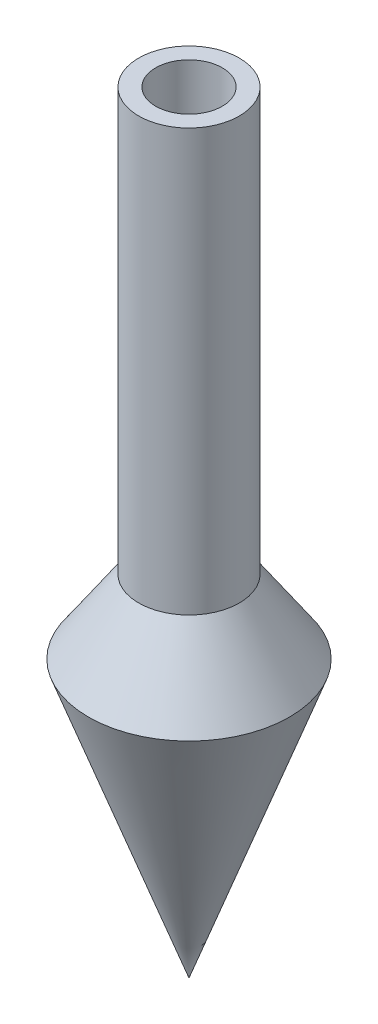
SolidWorks part; units mm, degrees
ref_plane "Front Plane" through (0, 0, 0) normal (0, 0, 1) x (1, 0, 0)
ref_plane "Top Plane" through (0, 0, 0) normal (0, 1, 0) x (1, 0, 0)
ref_plane "Right Plane" through (0, 0, 0) normal (1, 0, 0) x (0, 0, -1)
sketch "Sketch3" plane through (0, 0, 0) normal (0, 0, 1) x (1, 0, 0)
  line L0 (0, 0) -> (260.5989, 715.9895)
  line L1 (260.5989, 715.9895) -> (130.2994, 906.7875)
  line L2 (130.2994, 906.7875) -> (130.2994, 2000)
  line L5 (0, -730.4365) -> (0, 2203.2841) construction
  line L6 (0, 0) -> (0, 2000)
  line L7 (130.2994, 2000) -> (0, 2000)
  dimension "D1" = 2000
revolve "Revolve4" add sketch "Sketch3" angle 360 about L5
sketch "Sketch4" plane through (0, 2000, 0) normal (0, 1, 0) x (1, 0, 0)
  circle A0 centre (0, 0) radius 86.3632
extrude "Cut-Extrude1" cut sketch "Sketch4" against normal blind 1293
